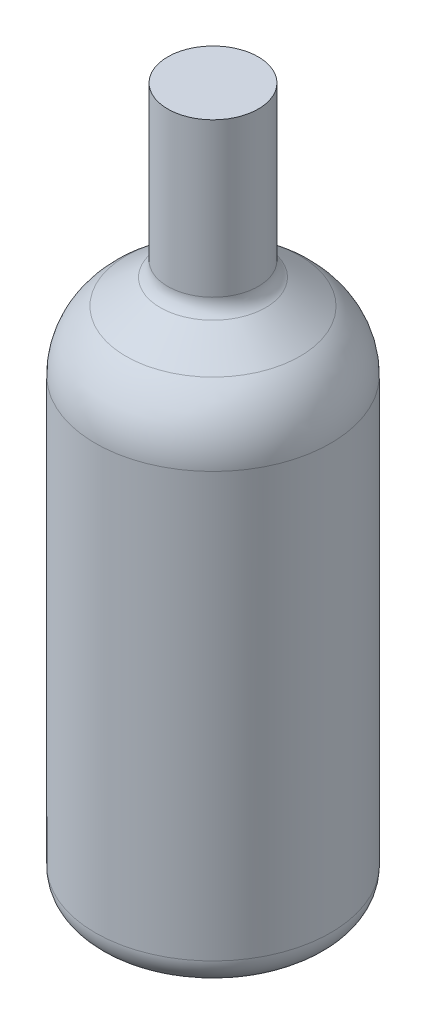
SolidWorks part; units mm, degrees
material "Verre"
ref_plane "Front" through (0, 0, 0) normal (0, 0, 1) x (1, 0, 0)
ref_plane "Top" through (0, 0, 0) normal (0, 1, 0) x (1, 0, 0)
ref_plane "Right" through (0, 0, 0) normal (1, 0, 0) x (0, 0, -1)
sketch "Esquisse1" plane through (0, 0, 0) normal (0, 1, 0) x (1, 0, 0)
  circle A0 centre (0, 0) radius 41.275
  dimension "D1" = 82.55
extrude "Boss.-Extru.1" add sketch "Esquisse1" along normal blind 158.75
sketch "Esquisse2" plane through (0, 0, 0) normal (0, 0, 1) x (1, 0, 0)
  line L0 (18.4894, 188.5981) -> (30.5427, 179.8294)
  line L1 (41.275, 158.75) -> (-41.275, 158.75) construction
  line L2 (15.875, 193.733) -> (15.875, 247.65)
  line L3 (15.875, 247.65) -> (0, 247.65)
  line L4 (0, 247.65) -> (0, 158.75)
  line L5 (41.275, 158.75) -> (0, 158.75)
  arc A0 (30.5427, 179.8294) -> (41.275, 158.75) centre (15.2077, 158.75) cw
  arc A1 (18.4894, 188.5981) -> (15.875, 193.733) centre (22.225, 193.733) cw
  point P10 (36.2132, 179.926)
  point P11 (5.3923, 155.5109)
  point P12 (20.5334, 187.5482)
  point P13 (15.875, 190.5)
  point P14 (27.6632, 181.232)
  point P17 (15.875, 190.5)
  point P18 (30.8743, 179.2228)
  point P19 (0, 0)
  dimension "D5" = 6.35
  dimension "D6" = 26.0673
  dimension "D1" = 88.9
  dimension "D2" = 31.75
  dimension "D3" = 15.875
  dimension "D4" = 41.275
revolve "Révolution1" add sketch "Esquisse2" angle 360 about L4
fillet "Congé1" radius 10 1 edges at (0, 0, 41.275)
